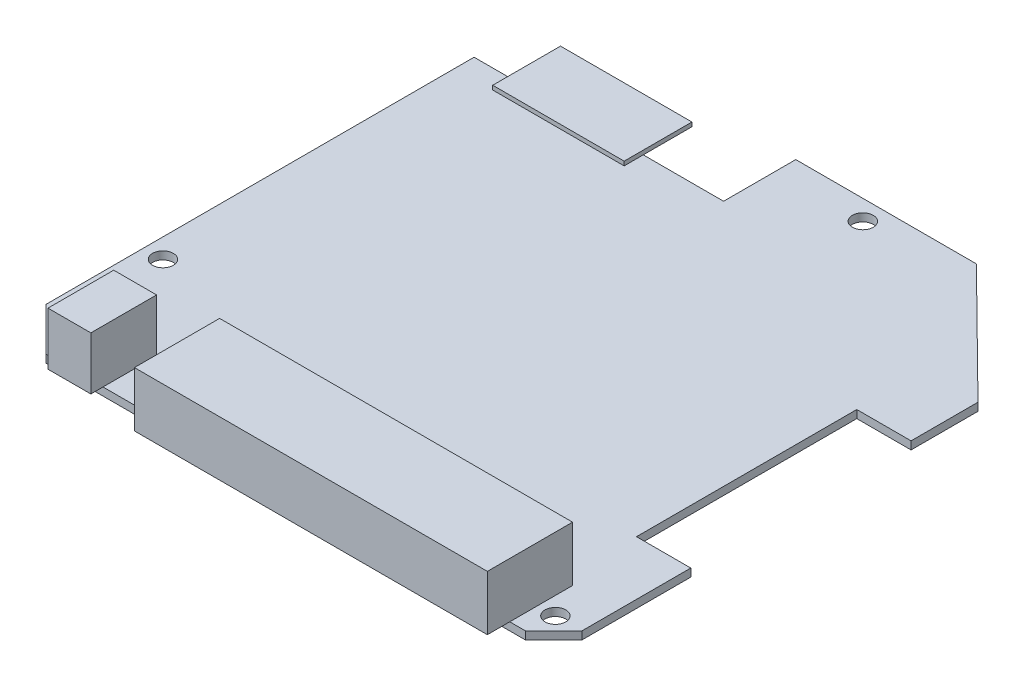
SolidWorks part; units mm, degrees
ref_plane "Front Plane" through (0, 0, 0) normal (0, 0, 1) x (1, 0, 0)
ref_plane "Top Plane" through (0, 0, 0) normal (0, 1, 0) x (1, 0, 0)
ref_plane "Right Plane" through (0, 0, 0) normal (1, 0, 0) x (0, 0, -1)
sketch "Sketch1" plane through (0, 0, 0) normal (0, 1, 0) x (1, 0, 0)
  line L0 (-57.4675, 41.6306) -> (-57.4675, -47.7125)
  line L1 (-57.4675, -47.7125) -> (-48.4872, -56.6928)
  line L2 (-48.4872, -56.6928) -> (51.5405, -56.6928)
  line L3 (51.5405, -56.6928) -> (57.4675, -50.7658)
  line L4 (57.4675, -50.7658) -> (57.4675, -28.0836)
  line L5 (57.4675, -28.0836) -> (46.1391, -28.0836)
  line L6 (46.1391, -28.0836) -> (46.1391, 17.8904)
  line L7 (46.1391, 17.8904) -> (57.4675, 17.8904)
  line L8 (57.4675, 17.8904) -> (57.4675, 31.8604)
  line L9 (57.4675, 31.8604) -> (32.2961, 56.6928)
  line L10 (32.2961, 56.6928) -> (-5.3975, 56.6928)
  line L11 (-5.3975, 56.6928) -> (-5.3975, 41.6306)
  line L12 (-5.3975, 41.6306) -> (-57.4675, 41.6306)
  line L13 (32.2961, 56.6928) -> (57.4675, 56.6928) construction
  line L14 (57.4675, 56.6928) -> (57.4675, 31.8604) construction
  line L15 (-57.4675, -47.7125) -> (-57.4675, -56.6928) construction
  line L16 (-57.4675, -56.6928) -> (-48.4872, -56.6928) construction
  line L17 (-57.4675, -56.6928) -> (57.4675, 56.6928) construction
  point P12 (0, 0)
  dimension "D1" = 37.6936
  dimension "D2" = 15.0622
  dimension "D3" = 52.07
  dimension "D4" = 113.3856
  dimension "D5" = 45.974
  dimension "D6" = 103.6066
  dimension "D7" = 8.382
  dimension "D8" = 12.7
  dimension "D9" = 13.97
  dimension "D10" = 135
  dimension "D11" = 22.6822
  dimension "D12" = 135
  dimension "D13" = 35.3589
  dimension "D14" = 114.935
extrude "PCB" add sketch "Sketch1" along normal blind 1.651
sketch "Sketch2" plane through (0, 1.651, 0) normal (0, 1, 0) x (1, 0, 0)
  line L1 (-5.3975, 41.6306) -> (-57.4675, 41.6306) construction
  line L2 (32.2961, 56.6928) -> (-5.3975, 56.6928) construction
  line L3 (-48.4872, -56.6928) -> (51.5405, -56.6928) construction
  line L4 (-5.3975, 56.6928) -> (-5.3975, 41.6306) construction
  line L5 (-57.4675, 41.6306) -> (-57.4675, -47.7125) construction
  line L6 (57.4675, -50.7658) -> (57.4675, -28.0836) construction
  circle A0 centre (-53.4035, -27.3685) radius 2.1717
  circle A1 centre (12.7508, 52.5399) radius 2.1717
  circle A2 centre (51.9938, -50.8635) radius 2.1717
  dimension "D1" = 68.9991
  dimension "D2" = 4.3434
  dimension "D3" = 4.1529
  dimension "D4" = 5.8293
  dimension "D5" = 18.1483
  dimension "D6" = 4.064
  dimension "D7" = 5.4737
extrude "MountHoles" cut sketch "Sketch2" against normal through all
sketch "Sketch3" plane through (0, 1.651, 0) normal (0, 1, 0) x (1, 0, 0)
  line L0 (-48.4872, -56.6928) -> (51.5405, -56.6928) construction
  line L1 (-25.3619, -43.5864) -> (48.2981, -43.5864)
  line L2 (-25.3619, -43.5864) -> (-25.3619, -61.3664)
  line L3 (-25.3619, -61.3664) -> (48.2981, -61.3664)
  line L4 (48.2981, -43.5864) -> (48.2981, -61.3664)
  line L6 (57.4675, -50.7658) -> (57.4675, -28.0836) construction
  dimension "D1" = 73.66
  dimension "D2" = 17.78
  dimension "D3" = 13.1064
  dimension "D4" = 9.1694
extrude "RJ45" add sketch "Sketch3" along normal blind 11.4554 separate body
sketch "Sketch4" plane through (0, 1.651, 0) normal (0, 1, 0) x (1, 0, 0)
  line L0 (-5.3975, 41.6306) -> (-57.4675, 41.6306) construction
  line L1 (-49.5935, 37.6428) -> (-22.1615, 37.6428)
  line L2 (-49.5935, 37.6428) -> (-49.5935, 51.7906)
  line L3 (-49.5935, 51.7906) -> (-22.1615, 51.7906)
  line L4 (-22.1615, 37.6428) -> (-22.1615, 51.7906)
  line L5 (-5.3975, 56.6928) -> (-5.3975, 41.6306) construction
  dimension "D1" = 27.432
  dimension "D2" = 14.1478
  dimension "D3" = 10.16
  dimension "D4" = 16.764
extrude "Ant" add sketch "Sketch4" along normal blind 0.8636 separate body
sketch "Sketch6" plane through (0, 1.651, 0) normal (0, 1, 0) x (1, 0, 0)
  line L0 (-57.4675, 41.6306) -> (-57.4675, -47.7125) construction
  line L1 (-45.5295, -45.5168) -> (-36.5887, -45.5168)
  line L2 (-45.5295, -45.5168) -> (-45.5295, -59.2328)
  line L3 (-45.5295, -59.2328) -> (-36.5887, -59.2328)
  line L4 (-36.5887, -45.5168) -> (-36.5887, -59.2328)
  line L5 (-48.4872, -56.6928) -> (51.5405, -56.6928) construction
  dimension "D1" = 13.716
  dimension "D2" = 8.9408
  dimension "D3" = 11.938
  dimension "D4" = 2.54
extrude "Power" add sketch "Sketch6" along normal blind 11.049 separate body
